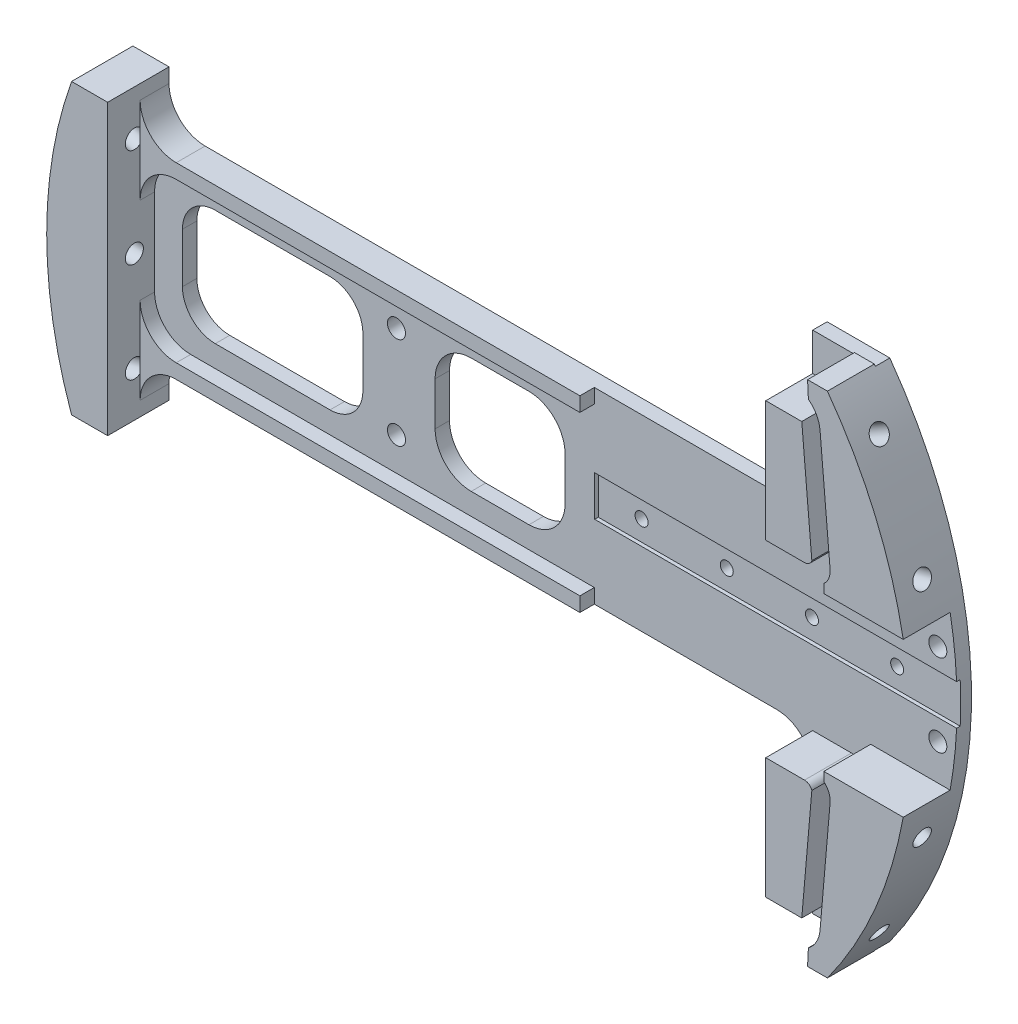
SolidWorks part; units mm, degrees
ref_plane "Front Plane" through (0, 0, 0) normal (0, 0, 1) x (1, 0, 0)
ref_plane "Top Plane" through (0, 0, 0) normal (0, 1, 0) x (1, 0, 0)
ref_plane "Right Plane" through (0, 0, 0) normal (1, 0, 0) x (0, 0, -1)
sketch "Sketch1" plane through (0, 0, 0) normal (0, 0, 1) x (1, 0, 0)
  line L0 (0, 0) -> (91.8237, 0) construction
  line L2 (-71.5726, 25.4) -> (-65.2226, 25.4)
  line L3 (50.546, 44.45) -> (50.546, 22.86)
  line L4 (50.546, -44.45) -> (50.546, -22.86)
  line L5 (44.196, -16.51) -> (-58.8726, -16.51)
  line L6 (50.546, 44.45) -> (61.5792, 44.45)
  line L7 (50.546, -44.45) -> (61.5792, -44.45)
  line L8 (-65.2226, -22.86) -> (-65.2226, -25.4)
  line L9 (44.196, 16.51) -> (-58.8726, 16.51)
  line L10 (-65.2226, 22.86) -> (-65.2226, 25.4)
  line L11 (-71.5726, -25.4) -> (-65.2226, -25.4)
  arc A0 (61.5792, -44.45) -> (61.5792, 44.45) centre (0, 0) ccw
  circle A1 centre (0, 0) radius 75.946 construction
  arc A2 (-71.5726, 25.4) -> (-71.5726, -25.4) centre (0, 0) ccw
  circle A3 centre (-22.6695, 8.128) radius 1.5875
  circle A4 centre (-22.6695, -8.128) radius 1.5875
  arc A5 (50.546, 22.86) -> (44.196, 16.51) centre (44.196, 22.86) cw
  arc A6 (-58.8726, 16.51) -> (-65.2226, 22.86) centre (-58.8726, 22.86) cw
  arc A7 (50.546, -22.86) -> (44.196, -16.51) centre (44.196, -22.86) ccw
  arc A8 (-58.8726, -16.51) -> (-65.2226, -22.86) centre (-58.8726, -22.86) ccw
  point P6 (75.946, 0)
  point P17 (0, 0)
  point P30 (50.546, -16.51)
  point P33 (-65.2226, -16.51)
  dimension "D1" = 75.946
  dimension "D8" = 151.892
  dimension "D11" = 75.946
  dimension "D13" = 6.35
  dimension "D7" = 3.175
  dimension ".125" = 3.175
  dimension "D2" = 27.94
  dimension "D3" = 6.35
  dimension "D4" = 11.0332
  dimension "D5" = 50.8
  dimension "D6" = 88.9
  dimension "D9" = 8.382
  dimension "D10" = 8.382
  dimension "D12" = 22.6695
  dimension "D14" = 22.6695
extrude "Boss-Extrude1" add sketch "Sketch1" along normal blind 2.54
sketch "Sketch2" plane through (0, 0, 2.54) normal (0, 0, 1) x (1, 0, 0)
  line L0 (60.2463, 17.78) -> (56.2059, 64.1603) construction
  line L1 (-13.9228, 0) -> (116.9939, 0) construction
  line L2 (35.7924, 17.78) -> (109.7023, 17.78) construction
  line L3 (61.8653, 17.78) -> (60.0951, 38.1)
  line L4 (58.6516, 17.5) -> (56.8815, 37.82)
  line L5 (56.8815, 37.82) -> (50.546, 37.82)
  line L6 (58.0471, 41.7789) -> (57.9008, 44.704)
  line L7 (57.9008, 44.704) -> (61.395, 44.704)
  line L8 (50.546, 37.82) -> (50.546, 16.5667)
  line L9 (50.546, 16.5667) -> (57.3661, 16.5667)
  line L10 (60.7595, 15.0941) -> (60.7595, 13.5449)
  line L11 (60.7595, 13.5449) -> (74.7284, 13.5449)
  line L12 (60.2463, -17.78) -> (56.2059, -64.1603) construction
  line L13 (60.7595, -13.5449) -> (74.7284, -13.5449)
  line L14 (60.7595, -15.0941) -> (60.7595, -13.5449)
  line L15 (50.546, -16.5667) -> (57.3661, -16.5667)
  line L16 (50.546, -37.82) -> (50.546, -16.5667)
  line L17 (57.9008, -44.704) -> (61.395, -44.704)
  line L18 (58.0471, -41.7789) -> (57.9008, -44.704)
  line L19 (56.8815, -37.82) -> (50.546, -37.82)
  line L20 (58.6516, -17.5) -> (56.8815, -37.82)
  line L21 (61.8653, -17.78) -> (60.0951, -38.1)
  line L22 (96.3863, 0) -> (96.3863, 82.276) construction
  arc A0 (61.5792, -44.45) -> (61.5792, 44.45) centre (0, 0) ccw construction
  arc A1 (60.0951, 38.1) -> (58.0471, 41.7789) centre (54.9639, 37.653) ccw
  arc A2 (57.3661, 16.5667) -> (58.6516, 17.5) centre (57.3661, 17.9187) ccw
  arc A3 (61.8653, 17.78) -> (60.7595, 15.0941) centre (58.7167, 17.5057) cw
  arc A4 (74.7284, 13.5449) -> (61.395, 44.704) centre (0, 0) ccw
  arc A5 (74.7284, -13.5449) -> (61.395, -44.704) centre (0, 0) cw
  arc A6 (61.8653, -17.78) -> (60.7595, -15.0941) centre (58.7167, -17.5057) ccw
  arc A7 (57.3661, -16.5667) -> (58.6516, -17.5) centre (57.3661, -17.9187) cw
  arc A8 (60.0951, -38.1) -> (58.0471, -41.7789) centre (54.9639, -37.653) cw
  point P0 (75.946, 0)
  point P1 (60.2463, 17.78)
  point P49 (96.3863, 44.704)
  dimension "D6" = 75.946
  dimension "D1" = 17.78
  dimension "D2" = 15.6997
  dimension "D3" = 85.021
  dimension "D4" = 1.6129
  dimension "D5" = 20.32
  dimension "D7" = 44.704
  dimension "D8" = 44.704
  dimension "D9" = 25.4
extrude "Boss-Extrude2" add sketch "Sketch2" along normal blind 8.255
sketch "Sketch3" plane through (0, 0, 2.54) normal (0, 0, 1) x (1, 0, 0)
  line L0 (-6.3906, 0) -> (92.2963, 0) construction
  line L1 (50.546, 44.45) -> (50.546, 22.86) construction
  line L2 (12.192, -3.55) -> (76.962, -3.55)
  line L3 (12.192, -3.55) -> (12.192, 3.55)
  line L4 (12.192, 3.55) -> (76.962, 3.55)
  line L5 (76.962, -3.55) -> (76.962, 3.55)
  line L6 (12.192, -3.55) -> (76.962, 3.55) construction
  line L7 (12.192, 3.55) -> (76.962, -3.55) construction
  point P3 (44.577, 0)
  dimension "D1" = 7.1
  dimension "D2" = 64.77
  dimension "D3" = 38.354
extrude "Cut-Extrude1" cut sketch "Sketch3" against normal blind 0.635
sketch "Sketch6" plane through (0, 0, 0) normal (0, 0, -1) x (-1, 0, 0)
  line L1 (102.4877, 0) -> (-122.8054, 0) construction
sketch "Sketch7" plane through (0, 0, 0) normal (0, 0, 1) x (1, 0, 0)
  line L0 (0, 0) -> (107.1474, 0) construction
  line L1 (0, 0) -> (65.9911, 38.1) construction
  dimension "D1" = 30
ref_plane "Plane2" through (65.7712, 37.973, 0) normal (0.866, 0.5, 0) x (0, 0, -1)
sketch "Sketch9" plane through (0, 0, 2.54) normal (0, 0, 1) x (1, 0, 0)
  line L0 (-35.0108, 0) -> (91.9546, 0) construction
  circle A0 centre (72.561, -7.239) radius 1.5875
  circle A4 centre (72.561, 7.239) radius 1.5875
  point P9 (74.93, 0)
  dimension "D6" = 3.175
  dimension "D1" = 3.302
  dimension "D4" = 74.93
  dimension "D7" = 7.239
extrude "Cut-Extrude4" cut sketch "Sketch9" against normal through all
sketch "Sketch4" plane through (0, 0, 1.905) normal (0, 0, 1) x (1, 0, 0)
  line L0 (12.192, 3.55) -> (12.192, -3.55) construction
  line L1 (-1.4827, 0) -> (103.4049, 0) construction
  circle A0 centre (19.812, 0) radius 1.143
  circle A1 centre (34.798, 0) radius 1.143
  circle A2 centre (49.784, 0) radius 1.143
  circle A3 centre (64.77, 0) radius 1.143
  point P2 (12.192, 0)
  dimension "D2" = 2.286
  dimension "D4" = 14.986
  dimension "D1" = 7.62
  dimension "D5" = 19.812
  dimension "D3" = 4
extrude "Cut-Extrude2" cut sketch "Sketch4" against normal blind 11.43
sketch "Sketch19" plane through (0, 0, 2.54) normal (0, 0, 1) x (1, 0, 0)
  line L0 (-71.5726, -25.4) -> (-65.2226, -25.4) construction
  line L3 (-71.5726, -25.4) -> (-65.2226, -25.4)
  line L4 (-65.2226, -25.4) -> (-65.2226, 25.4)
  line L5 (-65.2226, 25.4) -> (-71.5726, 25.4) construction
  line L6 (-65.2226, 25.4) -> (-71.5726, 25.4)
  circle A0 centre (0, 0) radius 75.946 construction
  arc A3 (-71.5726, 25.4) -> (-71.5726, -25.4) centre (0, 0) ccw
  point P0 (-65.2226, -25.4)
  point P6 (-71.5726, -25.4)
  dimension "D2" = 151.892
  dimension "D1" = 6.35
extrude "Boss-Extrude5" add sketch "Sketch19" along normal blind 8.255
ref_plane "Plane3" through (0, 0, 10.795) normal (0, 0, 1) x (1, 0, 0)
sketch "Sketch22" plane through (0, 0, 10.795) normal (0, 0, 1) x (1, 0, 0)
  line L1 (-75.946, -44.45) -> (75.946, -44.45) construction
  line L2 (-75.946, -44.45) -> (-75.946, 44.45) construction
  line L3 (-75.946, 44.45) -> (75.946, 44.45) construction
  line L4 (75.946, -44.45) -> (75.946, 44.45) construction
  line L5 (-75.946, -44.45) -> (75.946, 44.45) construction
  line L6 (-75.946, 44.45) -> (75.946, -44.45) construction
  point P0 (0, 0)
  dimension "D1" = 88.9
  dimension "D2" = 151.892
sketch "Sketch24" plane through (65.7712, 37.973, 0) normal (0.866, 0.5, 0) x (0, 0, -1)
  line L0 (0, -69.2844) -> (0, 7.7053) construction
  circle A0 centre (-6.0325, -2.2244) radius 1.6383
  dimension "D1" = 3.2766
  dimension "D2" = 6.0325
sketch "Sketch25" plane through (0, 0, 0) normal (0, 0, 1) x (1, 0, 0)
  line L0 (0, 0) -> (145.0129, 0) construction
  line L1 (0, 0) -> (140.0717, -37.5321) construction
  line L2 (0, 0) -> (125.5848, -72.5064) construction
  circle A0 centre (0, 0) radius 76.2 construction
  point P9 (0, 0)
  dimension "D1" = 152.4
  dimension "D2" = 3
ref_plane "Plane4" through (0, 0, 6.096) normal (0, 0, 1) x (1, 0, 0)
sketch "Sketch27" plane through (0, 0, 6.096) normal (0, 0, 1) x (1, 0, 0)
  line L0 (-98.5098, 0) -> (76.2, 0) construction
  line L1 (0, 0) -> (143.2275, -38.3777) construction
  line L2 (0, 0) -> (128.4143, -74.14) construction
  line L3 (0, 0) -> (143.2275, 38.3777) construction
  line L4 (0, 0) -> (128.4143, 74.14) construction
  line L5 (-95.1532, 25.4962) -> (73.6035, -19.722) construction
  line L6 (-95.1532, -25.4962) -> (73.6035, 19.722) construction
  circle A0 centre (0, 0) radius 76.2 construction
  point P5 (3.2671, -47.4697)
  point P10 (0, 0)
  point P13 (0, 0)
  point P17 (0, 0)
  point P19 (0, 0)
  dimension "D1" = 3
  dimension "D2" = 3
  dimension "D3" = 2
  dimension "D4" = 2
ref_plane "Plane5" through (65.7712, 37.973, 0) normal (0.866, 0.5, 0) x (0, 0, -1)
sketch "Sketch28" plane through (65.7712, 37.973, 0) normal (0.866, 0.5, 0) x (0, 0, -1)
  line L0 (0, -69.2844) -> (0, 7.7053) construction
  line L1 (-10.795, 8.0173) -> (-2.54, 8.0173) construction
  circle A0 centre (-6.0533, 0) radius 1.5875
  dimension "D1" = 3.175
  dimension "D2" = 6.0533
  dimension "D3" = 8.0173
extrude "Cut-Extrude12" cut sketch "Sketch28" against normal blind 7.62 contours A0
ref_plane "Plane6" through (73.3582, 19.6563, 0) normal (0.9659, 0.2588, 0) x (0, 0, -1)
ref_plane "Plane7" through (73.3582, -19.6563, 0) normal (0.9659, -0.2588, 0) x (0, 0, -1)
ref_plane "Plane8" through (65.7712, -37.973, 0) normal (0.866, -0.5, 0) x (0, 0, -1)
sketch "Sketch29" plane through (73.3582, 19.6563, 0) normal (0.9659, 0.2588, 0) x (0, 0, -1)
  circle A0 centre (-6.096, 0) radius 1.5875
  dimension "D1" = 3.175
extrude "Cut-Extrude13" cut sketch "Sketch29" against normal blind 10.16
ref_plane "Plane9" through (0, 0, 0) normal (0, 1, 0) x (1, 0, 0)
mirror "Mirror3" about plane through (0, 0, 0) normal (0, 1, 0) of "Cut-Extrude12", "Cut-Extrude13"
ref_plane "Plane10" through (-73.3582, 19.6563, 0) normal (-0.9659, 0.2588, 0) x (0, 0, 1)
ref_plane "Plane11" through (-75.946, 0, 0) normal (-1, 0, 0) x (0, 0, 1)
ref_plane "Plane12" through (-73.3582, -19.6563, 0) normal (-0.9659, -0.2588, 0) x (0, 0, 1)
sketch "Sketch30" plane through (-73.3582, 19.6563, 0) normal (-0.9659, 0.2588, 0) x (0, 0, 1)
  circle A0 centre (6.096, 0) radius 1.5875
  dimension "D1" = 3.175
extrude "Cut-Extrude14" cut sketch "Sketch30" against normal blind 12.7 contours A0
sketch "Sketch31" plane through (-75.946, 0, 0) normal (-1, 0, 0) x (0, 0, 1)
  circle A0 centre (6.096, 0) radius 1.5875
  dimension "D1" = 3.175
extrude "Cut-Extrude15" cut sketch "Sketch31" against normal blind 12.7
sketch "Sketch32" plane through (-73.3582, -19.6563, 0) normal (-0.9659, -0.2588, 0) x (0, 0, 1)
  circle A0 centre (6.096, 0) radius 1.5875
  dimension "D1" = 3.175
extrude "Cut-Extrude16" cut sketch "Sketch32" against normal blind 12.7
sketch "Sketch33" plane through (0, 0, 2.54) normal (0, 0, 1) x (1, 0, 0)
  line L0 (44.196, 16.51) -> (-58.8726, 16.51) construction
  line L1 (12.1373, 16.51) -> (-58.8726, 16.51)
  line L2 (44.196, 15.24) -> (-58.8726, 15.24) construction
  line L3 (12.1373, 13.97) -> (-58.8726, 13.97)
  line L4 (0, 0) -> (-34.589, 0) construction
  line L5 (-65.2226, 22.86) -> (-65.2226, 7.62)
  line L6 (12.1373, 13.97) -> (12.1373, 16.51)
  line L7 (12.1373, -13.97) -> (12.1373, -16.51)
  line L8 (44.196, 16.51) -> (-58.8726, 16.51) construction
  line L9 (44.196, -15.24) -> (-58.8726, -15.24) construction
  line L10 (12.1373, -16.51) -> (-58.8726, -16.51)
  line L11 (12.1373, -13.97) -> (-58.8726, -13.97)
  line L12 (-65.2226, -22.86) -> (-65.2226, -7.62)
  arc A0 (-65.2226, 22.86) -> (-58.8726, 16.51) centre (-58.8726, 22.86) ccw construction
  arc A1 (-65.2226, 22.86) -> (-58.8726, 16.51) centre (-58.8726, 22.86) ccw
  arc A2 (-65.2226, 7.62) -> (-58.8726, 13.97) centre (-58.8726, 7.62) cw
  arc A3 (-66.4926, 22.86) -> (-58.8726, 15.24) centre (-58.8726, 22.86) ccw construction
  arc A4 (-65.2226, -7.62) -> (-58.8726, -13.97) centre (-58.8726, -7.62) ccw
  arc A5 (-65.2226, -22.86) -> (-58.8726, -16.51) centre (-58.8726, -22.86) cw
  dimension "D2" = 71.0099
  dimension "D3" = 2.54
  dimension "D1" = 1.27
extrude "Boss-Extrude6" add sketch "Sketch33" along normal blind 2.54
sketch "Sketch34" plane through (0, 0, 2.54) normal (0, 0, 1) x (1, 0, 0)
  line L0 (12.1373, 16.51) -> (-58.8726, 16.51) construction
  line L1 (-54.5415, -10.16) -> (-34.3585, -10.16)
  line L2 (-60.325, -4.3765) -> (-60.325, 4.3765)
  line L3 (-54.5415, 10.16) -> (-34.3585, 10.16)
  line L4 (-28.575, -4.3765) -> (-28.575, 4.3765)
  line L5 (-60.325, -10.16) -> (-28.575, 10.16) construction
  line L6 (-60.325, 10.16) -> (-28.575, -10.16) construction
  line L8 (-9.525, 10.16) -> (0.635, 10.16)
  line L9 (-15.875, 3.81) -> (-15.875, -3.81)
  line L10 (-9.525, -10.16) -> (0.635, -10.16)
  line L11 (6.985, 3.81) -> (6.985, -3.81)
  line L12 (-15.875, 10.16) -> (6.985, -10.16) construction
  line L13 (-15.875, -10.16) -> (6.985, 10.16) construction
  arc A0 (-28.575, 4.3765) -> (-34.3585, 10.16) centre (-34.3585, 4.3765) ccw
  arc A1 (-28.575, -4.3765) -> (-34.3585, -10.16) centre (-34.3585, -4.3765) cw
  arc A2 (-54.5415, -10.16) -> (-60.325, -4.3765) centre (-54.5415, -4.3765) cw
  arc A3 (-54.5415, 10.16) -> (-60.325, 4.3765) centre (-54.5415, 4.3765) ccw
  arc A4 (-9.525, -10.16) -> (-15.875, -3.81) centre (-9.525, -3.81) cw
  arc A5 (6.985, -3.81) -> (0.635, -10.16) centre (0.635, -3.81) cw
  arc A6 (6.985, 3.81) -> (0.635, 10.16) centre (0.635, 3.81) ccw
  arc A7 (-9.525, 10.16) -> (-15.875, 3.81) centre (-9.525, 3.81) ccw
  point P0 (-44.45, 0)
  point P20 (-4.445, 0)
  dimension "D3" = 5.7835
  dimension "D8" = 6.35
  dimension "D1" = 20.32
  dimension "D2" = 6.35
  dimension "1.5" = 44.45
  dimension "1" = 31.75
  dimension "D4" = 20.32
  dimension "D5" = 22.86
  dimension "D6" = 6.35
  dimension "D7" = 12.7
extrude "Cut-Extrude17" cut sketch "Sketch34" against normal through all
equation "\"0.15inin\"=0.2"
equation "\"0.45inin\"=0.35"
equation "\"0.55inin\"=0.45"
equation "\"0.125inin\"=0.325"
